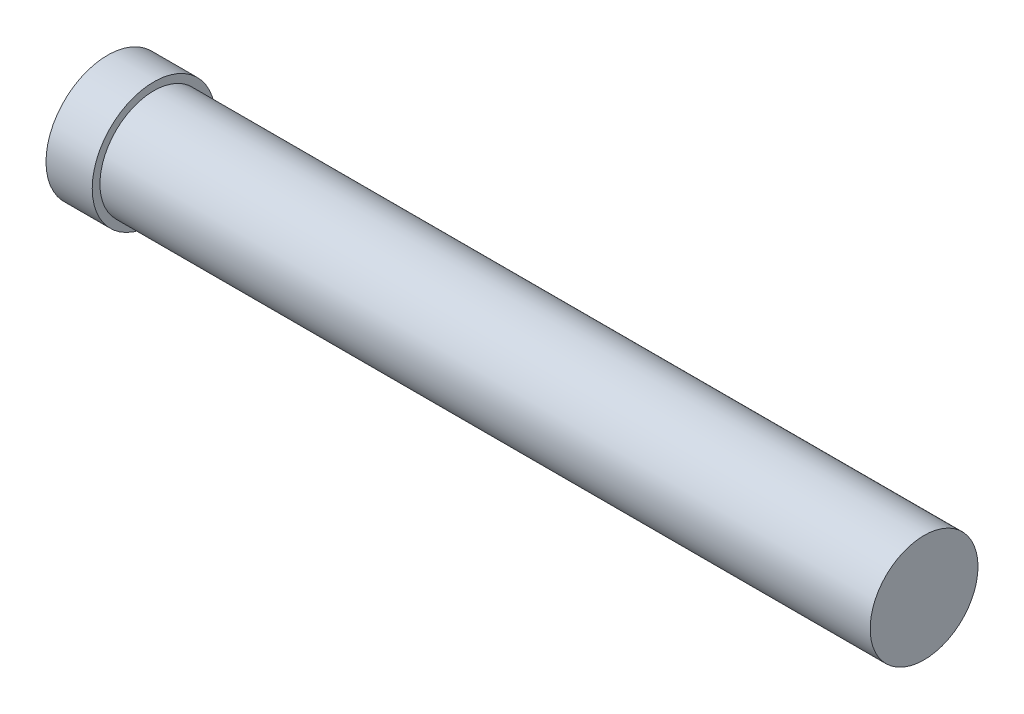
SolidWorks part; units mm, degrees
ref_plane "Front Plane" through (0, 0, 0) normal (0, 0, 1) x (1, 0, 0)
ref_plane "Top Plane" through (0, 0, 0) normal (0, 1, 0) x (1, 0, 0)
ref_plane "Right Plane" through (0, 0, 0) normal (1, 0, 0) x (0, 0, -1)
sketch "Sketch1" plane through (0, 0, 0) normal (1, 0, 0) x (0, 0, -1)
  circle A0 centre (0, 0) radius 3.5
  dimension "D1" = 7
extrude "Boss-Extrude1" add sketch "Sketch1" along normal blind 50
sketch "Sketch2" plane through (0, 0, 0) normal (-1, 0, 0) x (0, 0, 1)
  circle A0 centre (0, 0) radius 4
  dimension "D1" = 8
extrude "Boss-Extrude2" add sketch "Sketch2" along normal blind 3
